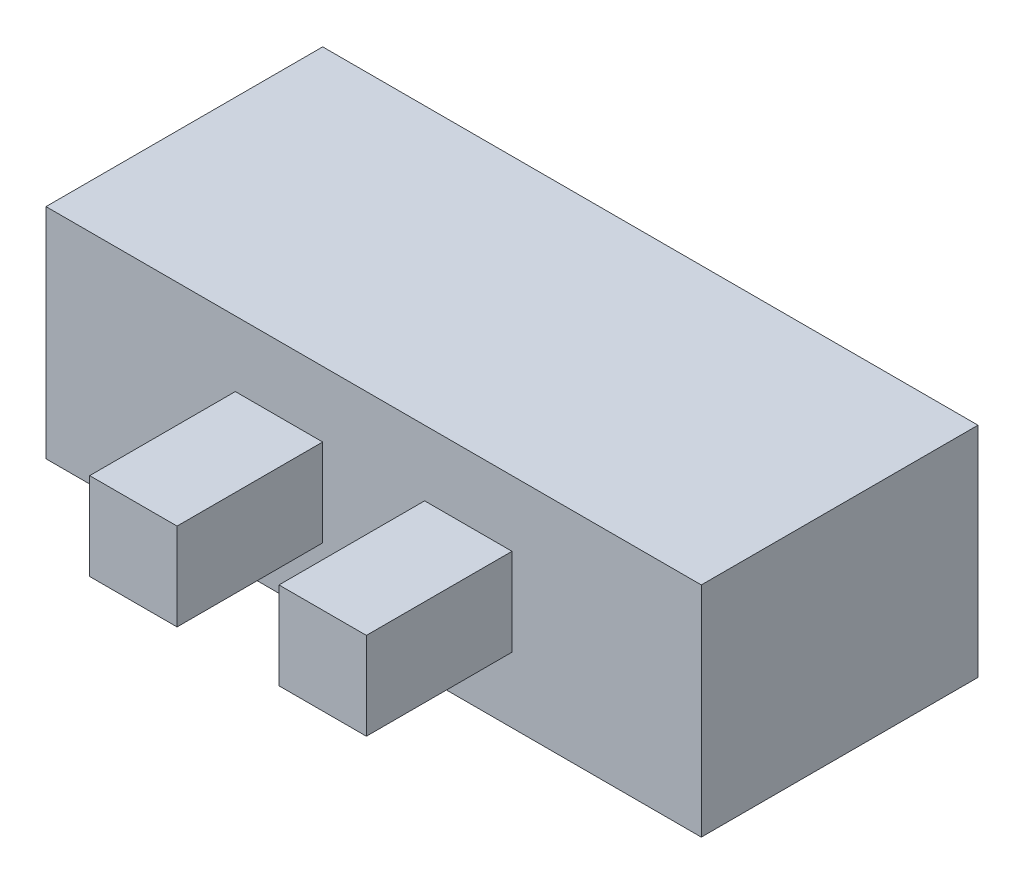
SolidWorks part; units mm, degrees
ref_plane "Front Plane" through (0, 0, 0) normal (0, 0, 1) x (1, 0, 0)
ref_plane "Top Plane" through (0, 0, 0) normal (0, 1, 0) x (1, 0, 0)
ref_plane "Right Plane" through (0, 0, 0) normal (1, 0, 0) x (0, 0, -1)
sketch "Sketch1" plane through (0, 0, 0) normal (0, 0, 1) x (1, 0, 0)
  line L1 (0, 0) -> (9, 0)
  line L2 (0, 0) -> (0, -3)
  line L3 (0, -3) -> (9, -3)
  line L4 (9, 0) -> (9, -3)
  dimension "D1" = 3
  dimension "D2" = 9
extrude "Boss-Extrude1" add sketch "Sketch1" along normal blind 3.8
sketch "Sketch2" plane through (0, 0, 3.8) normal (0, 0, 1) x (1, 0, 0)
  line L0 (5.2, -2.1) -> (6.4, -2.1)
  line L1 (2.6, -2.1) -> (3.8, -2.1)
  line L2 (2.6, -2.1) -> (2.6, -0.9)
  line L3 (2.6, -0.9) -> (3.8, -0.9)
  line L4 (3.8, -2.1) -> (3.8, -0.9)
  line L5 (0, 0) -> (0, -3) construction
  line L6 (0, -1.5) -> (10.0396, -1.5) construction
  line L7 (5.2, -2.1) -> (5.2, -0.9)
  line L8 (5.2, -0.9) -> (6.4, -0.9)
  line L9 (6.4, -2.1) -> (6.4, -0.9)
  line L10 (4.5, -3) -> (4.5, 2.1739) construction
  line L11 (0, -3) -> (9, -3) construction
  dimension "D1" = 1.2
  dimension "D2" = 1.2
  dimension "D3" = 3.8
extrude "Boss-Extrude2" add sketch "Sketch2" along normal blind 2
sketch "Sketch3" plane through (0, 0, 0) normal (0, 1, 0) x (1, 0, 0)
  line L0 (4.5, 0) -> (4.5, -9.8868) construction
  line L1 (9, 0) -> (0, 0) construction
ref_plane "Plane1" through (4.5, 0, 0) normal (1, 0, 0) x (0, 0, -1)
